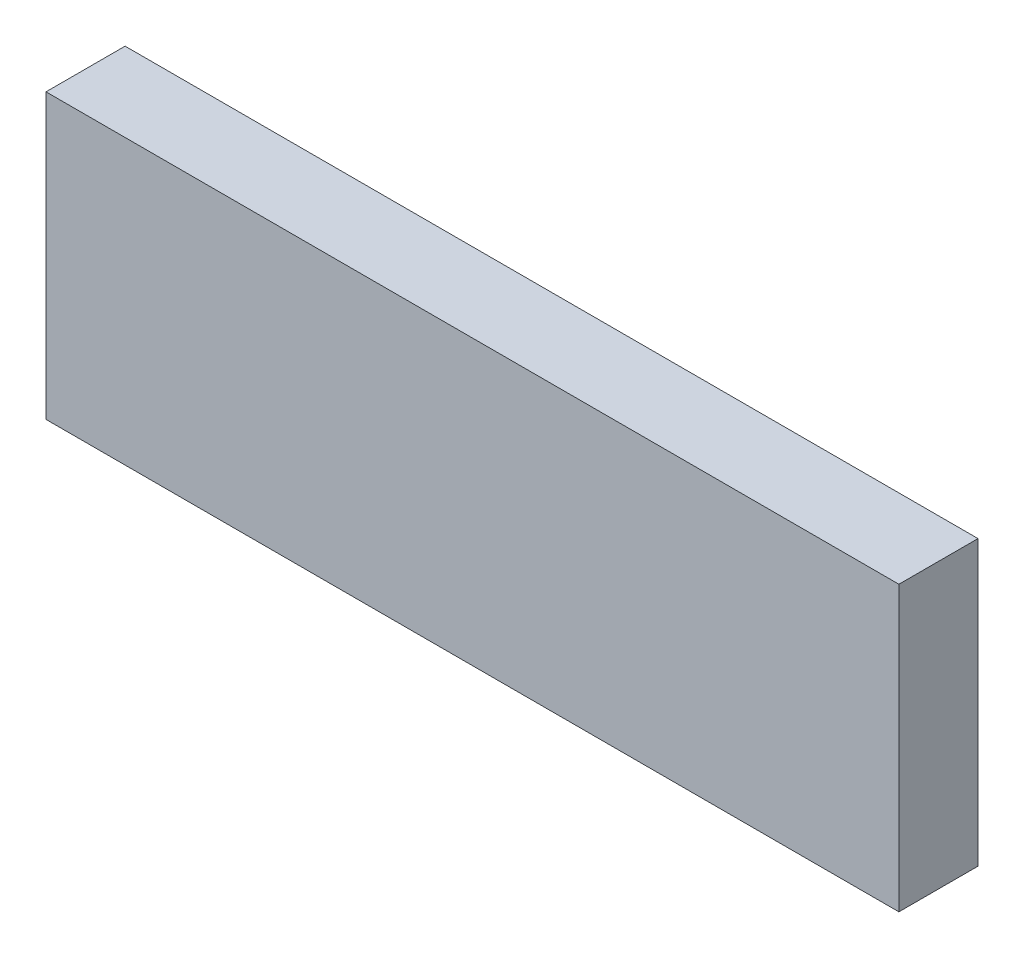
SolidWorks part; units mm, degrees
ref_plane "Front Plane" through (0, 0, 0) normal (0, 0, 1) x (1, 0, 0)
ref_plane "Top Plane" through (0, 0, 0) normal (0, 1, 0) x (1, 0, 0)
ref_plane "Right Plane" through (0, 0, 0) normal (1, 0, 0) x (0, 0, -1)
sketch "Sketch1" plane through (0, 0, 0) normal (0, 0, 1) x (1, 0, 0)
  line L1 (0, 0) -> (49.6, 0)
  line L2 (0, 0) -> (0, 16.5)
  line L3 (0, 16.5) -> (49.6, 16.5)
  line L4 (49.6, 0) -> (49.6, 16.5)
  dimension "D1" = 49.6
  dimension "D2" = 16.5
extrude "Boss-Extrude1" add sketch "Sketch1" along normal blind 4.6
equation "\"MDF\"= 4.8mm"
equation "\"Foamcore\"= 4.6mm"
equation "\"GMaterial\"= \"MDF\""
equation "\"PCB\" = 1.6mm"
equation "\"BaseWidth\" = 10in"
equation "\"SkidLength\" = 1in"
equation "\"SkidClearance\" = 0.4in"
equation "\"MotorMountLength\" = 2in"
equation "\"MotorMountWidth\" = \"GMaterial\""
equation "\"MotorMountHeight\" = 2.25in"
equation "\"UnoStackWidth\" = 77.4mm"
equation "\"UnoStackLength\" = 79.8mm"
equation "\"UnoStackHeight\" = 34.2mm"
equation "\"TallHexRiserHeight\" = 22.2mm"
equation "\"PingPongBallSize\" = 40mm"
equation "\"BarrelLength\" = 9in"
equation "\"BarrelSize\" = \"PingPongBallSize\""
equation "\"PlatformLength\" = 4in"
equation "\"PlatformWidth\" = 6in"
equation "\"WheelDiameter\"=2.99213"
equation "\"ServoMountHeight\"=2.49223"
equation "\"ServoGearHeight\" = 0.95330261in"
equation "\"ServoMountLength\"= 1.53774"
equation "\"PivotHoleRadius\"= 0.616358"
equation "\"PlatformMountHeight\" = 3.19"
equation "\"TensionOffSet\"= .3mm"
equation "\"MotorMountWedge\"=0.333333"
equation "\"LaserCutterOffset\"= .3mm"
equation "\"BumperWidth\"=11"
equation "\"PitcherWheelCompression\" = 2.5mm"
equation "\"BarrelToHopperDistance\" = 0.5405in"
equation "\"PitchingWheelWidth\" = 26.2mm"
equation "\"PitchingWheelDiameter\" = 65.5mm"
equation "\"PitchingWheelMountOffset\" = 8.4mm"
equation "\"PitchingWheelInnerDiameter\" = 45.5mm"
equation "\"PitchingWheelBoltShoulder\" = 4.5mm"
equation "\"BrassCouplingLength\" = 18mm"
equation "\"PitchingMotorHeight\" = 57.0mm"
equation "\"PitchingMotorShaftTopHeight\" = \"PitchingMotorHeight\" - 44.1mm"
equation "\"PitchingMotorBodyHeight\" = 38mm"
equation "\"PitchingMotorTopShoulderHeight\" = 40.6mm - \"PitchingMotorBodyHeight\" "
equation "\"PitchingMotorBottomShoulderHeight\" = 40.2mm - \"PitchingMotorBodyHeight\""
equation "\"PitchingMotorBottomShaftHeight\" = \"PitchingMotorHeight\" - \"PitchingMotorShaftTopHeight\" - \"PitchingMotorTopShoulderHeight\" - \"PitchingMotorBodyHeight\" - \"PitchingMotorBottomShoulderHeight\""
equation "\"PitchingMotorShaftDiameter\" = 2.2mm"
equation "\"PitchingMotorBodyDiameter\" = 27.4mm"
equation "\"PitchingMotorTopShoulderDiameter\" = 9.8mm"
equation "\"PitchingMotorBottomShoulderDiameter\" = 9.8mm"
equation "\"BrassCouplingHexSize\" = 12mm"
equation "\"BrassCouplingBoreSize\" = 3.17mm"
equation "\"PitchingMotorMountingHoleDistance\" = 16mm"
equation "\"Acrylic\" = 4.4mm"
equation "\"PitchingMotorDistance\" = \"PitchingWheelDiameter\" + \"PingPongBallSize\" - \"PitcherWheelCompression\"*2"
equation "\"PitchingMotorPlatformOffset\"=1"
equation "\"ServoPlatformOffset\"=1.64173"
equation "\"BallBearingDiameter\" = 22mm"
equation "\"BallBearingWidth\" = 9mm"
equation "\"BallBearingHexShoulder\" = 9mm - 5.9mm"
equation "\"BallBearingHexSize\" = .36in"
equation "\"PlatformMountFootLength\"=0.857143"
equation "\"WheelWidth\"= 26mm"
equation "\"ServoMountReductionBackHeight\"=2.25"
equation "\"PlatformBottomWidthThird\" =  0.857143in"
equation "\"PlatformMountBackReductionHeight\"= 2.5in"
equation "\"PlatformMountBackReductionWidth\"= 3/7in"
equation "\"PlatformMountFrontReductionWidth\" =  1.46226in"
equation "\"PlatformMountFrontReductionHeight\" = 2.5in"
equation "\"HopperLongWallLength\" = 8.646in"
equation "\"HopperShortWallLength\" = 0.9571in"
equation "\"HopperHeight\" = 3.50in - \"Foamcore\""
equation "\"HoperLongSlantLength\" = 7.064in"
equation "\"HopperBottomTemplateWidth\" = 8.03903165in"
equation "\"HopperBottomTemplateLength\" = 10.367854in"
equation "\"BeaconDiameter\" = 3.45in"
equation "\"HopperTopWidth\" = 11 - \"Foamcore\"*2 - \"BeaconDiameter\""
equation "\"D1@Boss-Extrude1\"=\"Foamcore\""
equation "\"BarrelCapHeight\" = 0.6496063in"
equation "\"D1@Sketch1\"=\"PingPongBallSize\"+\"MDF\"*2"
equation "\"D2@Sketch1\"=\"BarrelCapHeight\""
